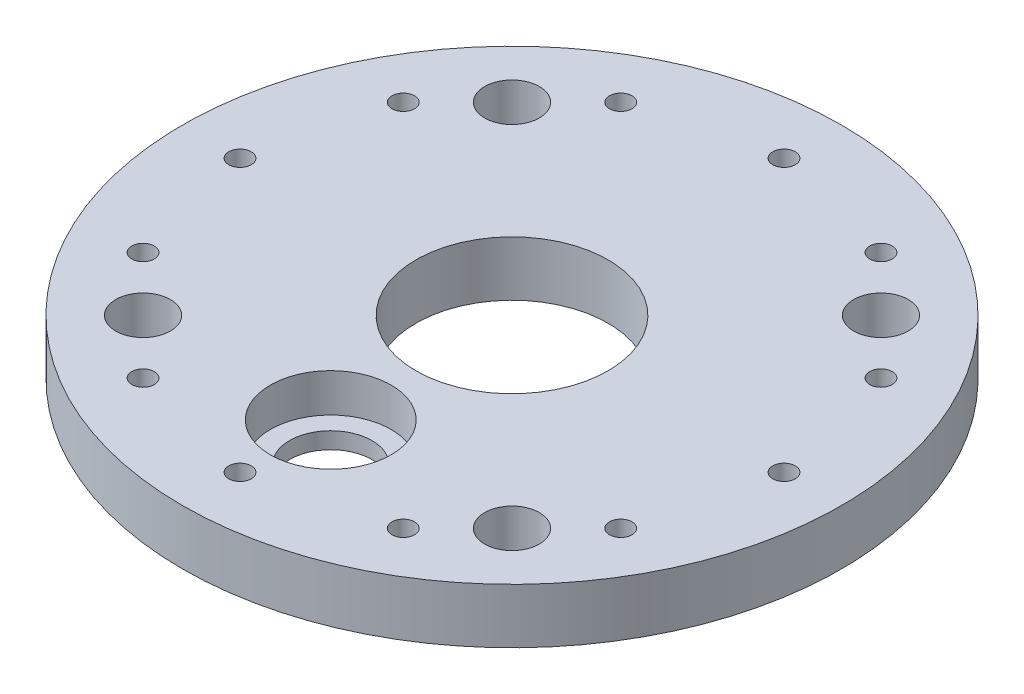
SolidWorks part; units mm, degrees
material "PLA+"
ref_plane "Front Plane" through (0, 0, 0) normal (0, 0, 1) x (1, 0, 0)
ref_plane "Top Plane" through (0, 0, 0) normal (0, 1, 0) x (1, 0, 0)
ref_plane "Right Plane" through (0, 0, 0) normal (1, 0, 0) x (0, 0, -1)
sketch "Sketch1" plane through (0, 0, 0) normal (0, 1, 0) x (1, 0, 0)
  circle A0 centre (0, 0) radius 60
  dimension "D1" = 120
extrude "Boss-Extrude1" add sketch "Sketch1" along normal blind 10
sketch "Sketch2" plane through (0, 10, 0) normal (0, 1, 0) x (1, 0, 0)
  circle A0 centre (0, -33) radius 11
  dimension "D2" = 22
  dimension "D1" = 33
extrude "Cut-Extrude1" cut sketch "Sketch2" against normal blind 7
sketch "Sketch3" plane through (0, 3, 0) normal (0, 1, 0) x (1, 0, 0)
  circle A0 centre (0, -33) radius 7.5
  dimension "D1" = 15
extrude "Cut-Extrude2" cut sketch "Sketch3" against normal through all
sketch "Sketch5" plane through (0, 10, 0) normal (0, 1, 0) x (1, 0, 0)
  line L0 (0, 0) -> (-33.5876, -33.5876) construction
  line L1 (0, 0) -> (0, -33) construction
  line L2 (-9.8995, 9.8995) -> (-43.4871, -23.6881) construction
  line L3 (9.8995, -9.8995) -> (-23.6881, -43.4871) construction
  circle A0 centre (-33.5876, -33.5876) radius 4.975
  circle A2 centre (-43.4871, -23.6881) radius 2.05
  circle A3 centre (-23.6881, -43.4871) radius 2.05
  dimension "D2" = 9.95
  dimension "D6" = 4.1
  dimension "D7" = 4.1
  dimension "D1" = 47.5
  dimension "D3" = 45
  dimension "D4" = 14
  dimension "D5" = 14
extrude "Cut-Extrude4" cut sketch "Sketch5" against normal through all
sketch "Sketch6" plane through (0, 10, 0) normal (0, 1, 0) x (1, 0, 0)
  circle A0 centre (0, -49.52) radius 2.05
  point P5 (0, 0)
  dimension "D2" = 4.1
  dimension "D1" = 49.52
extrude "Cut-Extrude5" cut sketch "Sketch6" against normal through all
pattern_circular "CirPattern1" count 4 over 360 about axis through (0, 0, 0) along (0, 1, 0) of "Cut-Extrude4", "Cut-Extrude5"
sketch "Sketch7" plane through (0, 10, 0) normal (0, 1, 0) x (1, 0, 0)
  circle A0 centre (0, 0) radius 17.5
  dimension "D1" = 35
extrude "Cut-Extrude6" cut sketch "Sketch7" against normal through all contours A0
